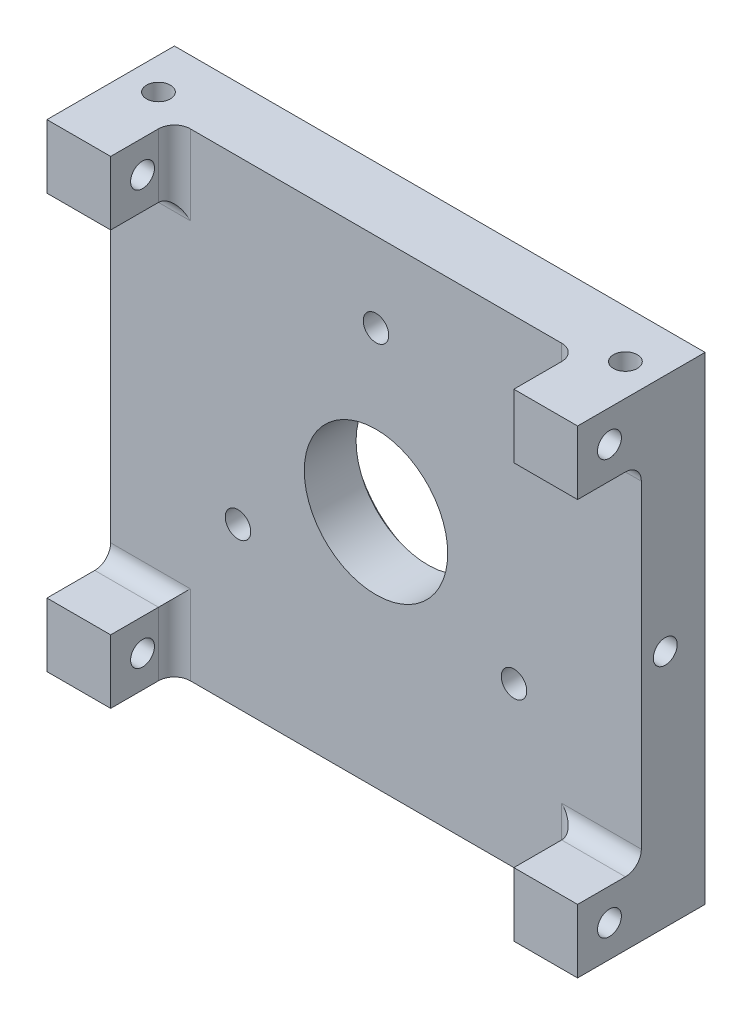
SolidWorks part; units mm, degrees
material "6061 合金"
ref_plane "前视基准面" through (0, 0, 0) normal (0, 0, 1) x (1, 0, 0)
ref_plane "上视基准面" through (0, 0, 0) normal (0, 1, 0) x (1, 0, 0)
ref_plane "右视基准面" through (0, 0, 0) normal (1, 0, 0) x (0, 0, -1)
sketch "草图1" plane through (0, 0, 0) normal (0, 0, 1) x (1, 0, 0)
  line L0 (0, 0) -> (0, 20) construction
  line L4 (33.3, -30) -> (-33.3, -30)
  line L5 (33.3, -30) -> (33.3, 30)
  line L6 (33.3, 30) -> (-33.3, 30)
  line L7 (-33.3, -30) -> (-33.3, 30)
  line L8 (33.3, -30) -> (-33.3, 30) construction
  line L9 (33.3, 30) -> (-33.3, -30) construction
  line L10 (0, 0) -> (-17.3205, -10) construction
  line L11 (0, 0) -> (17.3205, -10) construction
  circle A0 centre (0, 0) radius 20 construction
  circle A5 centre (0, 20) radius 1.6
  circle A7 centre (17.3205, -10) radius 1.6
  circle A8 centre (-17.3205, -10) radius 1.6
  circle A9 centre (0, 0) radius 9
  point P0 (0, 0)
  dimension "D1" = 40
  dimension "D2" = 3.2
  dimension "D3" = 3
  dimension "D4" = 66.6
  dimension "D5" = 60
  dimension "D6" = 18
  dimension "D7" = 120
  dimension "D8" = 120
extrude "凸台-拉伸1" add sketch "草图1" along normal blind 8
sketch "草图3" plane through (0, 0, 8) normal (0, 0, 1) x (1, 0, 0)
  line L0 (-25.3, 30) -> (-25.3, 22)
  line L1 (33.3, 30) -> (-33.3, 30) construction
  line L2 (-25.3, 22) -> (-33.3, 22)
  line L3 (-33.3, 30) -> (-33.3, -30) construction
  line L4 (-33.3, 22) -> (-33.3, 30)
  line L5 (-33.3, 30) -> (-25.3, 30)
  line L6 (0, 0) -> (14.3383, 0) construction
  line L7 (0, 0) -> (0, 41.1614) construction
  line L8 (-33.3, -30) -> (-25.3, -30)
  line L9 (-33.3, -22) -> (-33.3, -30)
  line L10 (-25.3, -22) -> (-33.3, -22)
  line L11 (-25.3, -30) -> (-25.3, -22)
  line L12 (25.3, -30) -> (25.3, -22)
  line L13 (25.3, -22) -> (33.3, -22)
  line L14 (33.3, -22) -> (33.3, -30)
  line L15 (33.3, -30) -> (25.3, -30)
  line L16 (33.3, 30) -> (25.3, 30)
  line L17 (33.3, 22) -> (33.3, 30)
  line L18 (25.3, 22) -> (33.3, 22)
  line L19 (25.3, 30) -> (25.3, 22)
  dimension "D1" = 8
  dimension "D2" = 8
extrude "凸台-拉伸2" add sketch "草图3" along normal blind 8
sketch "草图4" plane through (-33.3, 0, 0) normal (-1, 0, 0) x (0, 0, 1)
  line L0 (5, 30) -> (5, -30) construction
  line L1 (16, 30) -> (0, 30) construction
  line L2 (16, -30) -> (0, -30) construction
  line L3 (0, 30) -> (0, -30) construction
  line L4 (16, 30) -> (16, 22) construction
  line L5 (0, 0) -> (15.3449, 0) construction
  circle A1 centre (12, 26) radius 1.5
  circle A2 centre (12, -26) radius 1.5
  circle A4 centre (5, 0) radius 1.5
  dimension "D2" = 3
  dimension "D4" = 3
  dimension "D1" = 5
  dimension "D5" = 4
  dimension "D6" = 4
extrude "切除-拉伸1" cut sketch "草图4" against normal blind 8
sketch "草图5" plane through (33.3, 0, 0) normal (1, 0, 0) x (0, 0, -1)
  circle A0 centre (-12, -26) radius 1.5 construction
  circle A3 centre (-12, 26) radius 1.5 construction
  circle A4 centre (-12, -26) radius 1.5
  circle A7 centre (-12, 26) radius 1.5
  circle A8 centre (-5, 0) radius 1.5 construction
  circle A9 centre (-5, 0) radius 1.5
extrude "切除-拉伸2" cut sketch "草图5" against normal blind 8
sketch "草图6" plane through (0, 30, 0) normal (0, 1, 0) x (1, 0, 0)
  line L0 (-33.3, -16) -> (-33.3, 0) construction
  line L1 (33.3, 0) -> (-33.3, 0) construction
  line L2 (0, 0) -> (0, -8) construction
  line L3 (25.3, -8) -> (-25.3, -8) construction
  circle A0 centre (-29.3, -6) radius 1.5
  circle A1 centre (29.3, -6) radius 1.5
  dimension "D1" = 3
  dimension "D2" = 4
  dimension "D3" = 6
extrude "切除-拉伸3" cut sketch "草图6" against normal blind 8
sketch "草图7" plane through (0, -30, 0) normal (0, -1, 0) x (1, 0, 0)
  circle A0 centre (29.3, 6) radius 1.5 construction
  circle A1 centre (-29.3, 6) radius 1.5 construction
  circle A2 centre (29.3, 6) radius 1.5
  circle A3 centre (-29.3, 6) radius 1.5
extrude "切除-拉伸4" cut sketch "草图7" against normal blind 8
fillet "圆角1" radius 2 8 edges at (-29.3, 22, 8) (-25.3, 26, 8) (-25.3, -26, 8) (-29.3, -22, 8) (29.3, -22, 8) (25.3, -26, 8) (29.3, 22, 8) (25.3, 26, 8)
sketch "草图8" plane through (0, 0, 0) normal (0, 0, -1) x (-1, 0, 0)
  circle A0 centre (0, 0) radius 11
  dimension "D1" = 22
extrude "切除-拉伸5" cut sketch "草图8" against normal blind 1.5
